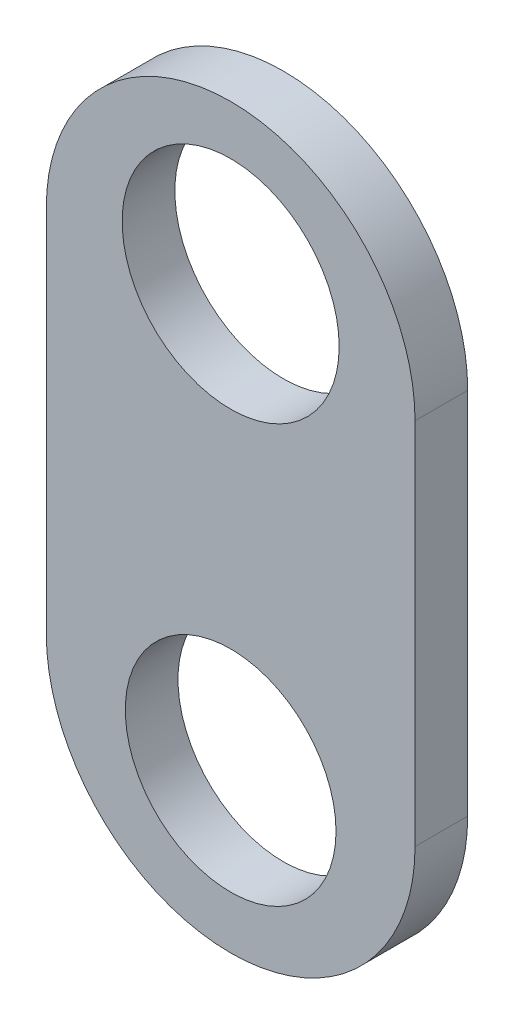
SolidWorks part; units mm, degrees
ref_plane "Front Plane" through (0, 0, 0) normal (0, 0, 1) x (1, 0, 0)
ref_plane "Top Plane" through (0, 0, 0) normal (0, 1, 0) x (1, 0, 0)
ref_plane "Right Plane" through (0, 0, 0) normal (1, 0, 0) x (0, 0, -1)
sketch "Sketch1" plane through (0, 0, 0) normal (0, 0, 1) x (1, 0, 0)
  line L0 (0, -22.225) -> (0, 22.225) construction
  line L5 (-22.225, -22.225) -> (-22.225, 22.225)
  line L6 (22.225, -22.225) -> (22.225, 22.225)
  line L7 (15.276, 0) -> (-14.4196, 0) construction
  arc A0 (-22.225, -22.225) -> (22.225, -22.225) centre (0, -22.225) ccw
  arc A1 (22.225, 22.225) -> (-22.225, 22.225) centre (0, 22.225) ccw
  circle A2 centre (0, 25.4) radius 13.081
  circle A3 centre (0, -25.4) radius 12.7
  point P2 (0, 0)
  point P5 (0, -22.225)
  point P9 (0, 44.45)
  point P10 (0, -44.45)
  point P15 (0, 0)
  point P16 (0, 0)
  dimension "D1" = 88.9
  dimension "D3" = 26.162
  dimension "D4" = 25.4
  dimension "D2" = 44.45
  dimension "D5" = 50.8
extrude "Boss-Extrude1" add sketch "Sketch1" along normal blind 6.35 contours L6 A1 L5 A0 A3 A2
equation "\"DA\"= 1.033'Bracket Feature A diameter"
equation "\"HoleA\"= \"DA\"'Top Hole Diameter"
equation "\"LinkWidth\"= 1.75'Overall width of link"
equation "\"LinkThick\"= 0.25'Thickness of link"
equation "\"HoleShaft\"= 1.00'Bottom hole diameter (shaft interface)"
equation "\"HoleSpacing\"= 2.00'Center to center distance between holes"
equation "\"LinkLength\"= 3.50'Overal Length of link"
equation "\"EndRadius\"= \"LinkWidth\" / 2'Radius of the outsid ends of the link"
